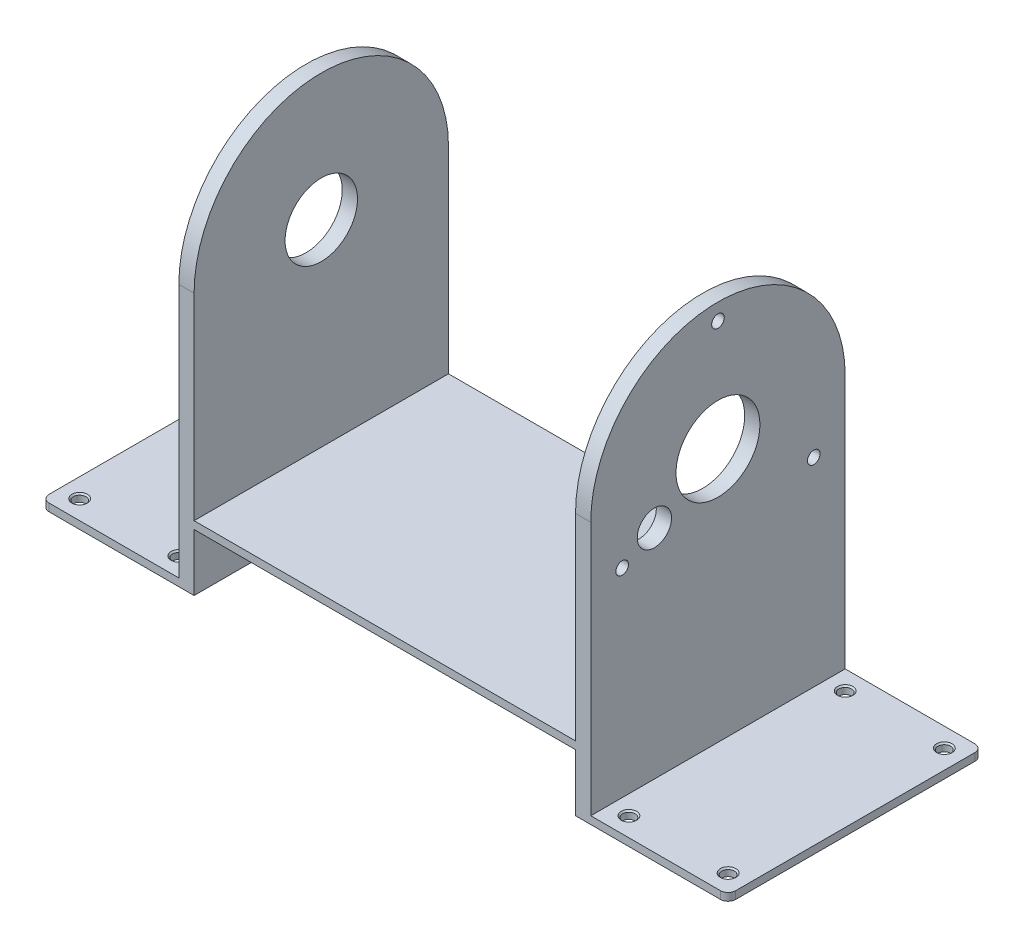
SolidWorks part; units mm, degrees
material "ABS"
ref_plane "前视基准面" through (0, 0, 0) normal (0, 0, 1) x (1, 0, 0)
ref_plane "上视基准面" through (0, 0, 0) normal (0, 1, 0) x (1, 0, 0)
ref_plane "右视基准面" through (0, 0, 0) normal (1, 0, 0) x (0, 0, -1)
sketch "草图1" plane through (0, 0, 0) normal (0, 1, 0) x (1, 0, 0)
  line L1 (-20, -33.35) -> (20, -33.35)
  line L2 (-20, -33.35) -> (-20, 33.35)
  line L3 (-20, 33.35) -> (20, 33.35)
  line L4 (20, -33.35) -> (20, 33.35)
  line L5 (-20, -33.35) -> (20, 33.35) construction
  line L6 (-20, 33.35) -> (20, -33.35) construction
  point P0 (0, 0)
  dimension "D1" = 40
  dimension "D2" = 66.7
extrude "凸台-拉伸1" add sketch "草图1" along normal blind 2
sketch "草图2" plane through (0, 2, 0) normal (0, 1, 0) x (1, 0, 0)
  line L0 (-20, -33.35) -> (20, -33.35) construction
  line L1 (-20, 33.35) -> (-16, 33.35)
  line L2 (-20, 33.35) -> (-20, -33.35)
  line L3 (-20, -33.35) -> (-16, -33.35)
  line L4 (-16, 33.35) -> (-16, -33.35)
  dimension "D1" = 4
extrude "凸台-拉伸2" add sketch "草图2" along normal blind 100
sketch "草图5" plane through (-20, 0, 0) normal (-1, 0, 0) x (0, 0, 1)
  line L0 (33.35, 102) -> (33.35, 0) construction
  line L1 (-33.35, 102) -> (33.35, 102) construction
  line L2 (33.35, 68.65) -> (33.35, 102)
  line L3 (33.35, 102) -> (0, 102)
  line L4 (0, 102) -> (-33.35, 102)
  line L5 (-33.35, 102) -> (-33.35, 68.65)
  circle A0 centre (0, 68.65) radius 33.35
  line M3 (33.35, 0) -> (33.35, 102)
  line M4 (33.35, 102) -> (-33.35, 102)
  line M5 (-33.35, 102) -> (-33.35, 0)
  dimension "D1" = 66.7
extrude "切除-拉伸1" cut sketch "草图5" against normal through all and the other way through all contours A0 M4 M5 | A0 M3 M4 | L2 L3 L4 L5
sketch "草图6" plane through (-20, 0, 0) normal (-1, 0, 0) x (0, 0, 1)
  line L0 (0, 68.65) -> (0, 97.65) construction
  line L1 (0, 68.65) -> (25.1147, 54.15) construction
  line L2 (0, 68.65) -> (-25.1147, 54.15) construction
  circle A0 centre (0, 68.65) radius 29 construction
  point P7 (0, 97.65)
  point P8 (25.1147, 54.15)
  point P9 (-25.1147, 54.15)
  point P10 (0, 68.65)
  dimension "D1" = 58
  dimension "D2" = 120
  dimension "D3" = 120
hole_wizard "M4 螺纹孔1" positions "草图7" profile "草图8" tap size "M4" standard "GB" end condition through all
sketch "草图7" plane through (-20, 0, 0) normal (-1, 0, 0) x (0, 0, 1)
  point P0 (0, 97.65)
  point P3 (25.1147, 54.15)
  point P6 (-25.1147, 54.15)
sketch "草图8" plane through (-20, 97.65, 0) normal (0, 1, 0) x (0, 0, 1)
  line L0 (0, 0) -> (0, 40)
  line L1 (0, 40) -> (1.65, 40)
  line L2 (1.65, 40) -> (1.65, 0.375)
  line L3 (1.65, 0.375) -> (2.025, 0)
  line L5 (2.025, 0) -> (0, 0)
  line L6 (-1.65, 0.375) -> (-2.025, 0) construction
  line L11 (0, -6.35) -> (0, 107.95) construction
  dimension "通孔螺纹孔钻头直径" = 3.3
  dimension "通孔螺纹孔钻头深度" = 40
  dimension "近端锥形沉头孔直径" = 4.05
  dimension "近端锥形沉头孔角度" = 90
sketch "草图9" plane through (0, 2, 0) normal (0, 1, 0) x (1, 0, 0)
  line L0 (-16, -33.35) -> (20, -33.35) construction
  line L1 (-11, 28.35) -> (15, 28.35) construction
  line L2 (-11, 28.35) -> (-11, -28.35) construction
  line L3 (-11, -28.35) -> (15, -28.35) construction
  line L4 (15, 28.35) -> (15, -28.35) construction
  line L5 (20, 33.35) -> (-16, 33.35) construction
  line L6 (20, -33.35) -> (20, 33.35) construction
  line L7 (-16, -33.35) -> (-16, 33.35) construction
  point P12 (-50.2188, 7.1013)
  point P13 (-11, 28.35)
  point P14 (-11, -28.35)
  point P15 (15, -28.35)
  point P16 (15, 28.35)
  dimension "D1" = 5
  dimension "D2" = 5
  dimension "D3" = 5
  dimension "D4" = 5
hole_wizard "M4 螺纹孔2" positions "草图9" profile "草图10" tap size "M4" standard "GB" end condition through all
sketch "草图10" plane through (15, 2, -28.35) normal (1, 0, 0) x (0, 0, 1)
  line L0 (0, 0) -> (0, 2)
  line L1 (0, 2) -> (1.65, 2)
  line L2 (1.65, 2) -> (1.65, 0.375)
  line L3 (1.65, 0.375) -> (2.025, 0)
  line L5 (2.025, 0) -> (0, 0)
  line L6 (-1.65, 0.375) -> (-2.025, 0) construction
  line L11 (0, -6.35) -> (0, 107.95) construction
  dimension "通孔螺纹孔钻头直径" = 3.3
  dimension "通孔螺纹孔钻头深度" = 2
  dimension "近端锥形沉头孔直径" = 4.05
  dimension "近端锥形沉头孔角度" = 90
sketch "草图11" plane through (-20, 0, 0) normal (-1, 0, 0) x (0, 0, 1)
  line L0 (-33.35, 68.65) -> (-33.35, 0) construction
  line L1 (-33.35, 17) -> (33.35, 17)
  line L2 (-33.35, 17) -> (-33.35, 15)
  line L3 (-33.35, 15) -> (33.35, 15)
  line L4 (33.35, 17) -> (33.35, 15)
  line L5 (33.35, 68.65) -> (33.35, 0) construction
  line L6 (-33.35, 0) -> (33.35, 0) construction
  dimension "D1" = 2
  dimension "D2" = 15
extrude "凸台-拉伸3" add sketch "草图11" along normal blind 100 contours L1 L4 L3 L2
ref_plane "基准面1" through (-70, 0, 0) normal (-1, 0, 0) x (0, 0, 1)
sketch "草图13" plane through (0, 0, 0) normal (0, 1, 0) x (1, 0, 0)
  line L0 (-120, -33.35) -> (-20, -33.35) construction
  line L1 (-120, 33.35) -> (-160, 33.35)
  line L2 (-120, 33.35) -> (-120, -33.35)
  line L3 (-120, -33.35) -> (-160, -33.35)
  line L4 (-160, 33.35) -> (-160, -33.35)
  dimension "D1" = 40
extrude "凸台-拉伸4" add sketch "草图13" along normal blind 2 separate body
sketch "草图14" plane through (0, 2, 0) normal (0, 1, 0) x (1, 0, 0)
  line L0 (-120, 33.35) -> (-120, -33.35) construction
  line L1 (-120, 33.35) -> (-124, 33.35)
  line L2 (-120, 33.35) -> (-120, -33.35)
  line L3 (-120, -33.35) -> (-124, -33.35)
  line L4 (-124, 33.35) -> (-124, -33.35)
  line L5 (-160, -33.35) -> (-120, -33.35) construction
  line L6 (-120, 33.35) -> (-160, 33.35) construction
  dimension "D1" = 4
extrude "凸台-拉伸5" add sketch "草图14" along normal blind 100
sketch "草图15" plane through (-124, 0, 0) normal (-1, 0, 0) x (0, 0, 1)
  line L0 (-33.35, 102) -> (33.35, 102) construction
  line L1 (33.35, 102) -> (33.35, 2) construction
  line L3 (33.35, 68.65) -> (33.35, 102)
  line L4 (33.35, 102) -> (0, 102)
  line L5 (0, 102) -> (-33.35, 102)
  line L6 (-33.35, 102) -> (-33.35, 61.9505)
  circle A0 centre (0, 68.65) radius 33.35
  line M3 (33.35, 2) -> (33.35, 102)
  line M4 (33.35, 102) -> (-33.35, 102)
  line M5 (-33.35, 102) -> (-33.35, 2)
  dimension "D1" = 66.7
extrude "切除-拉伸2" cut sketch "草图15" against normal through all and the other way through all contours A0 M4 M5 | A0 M3 M4 | L3 L4 L5 L6
sketch "草图16" plane through (0, 2, 0) normal (0, 1, 0) x (1, 0, 0)
  line L0 (-160, -33.35) -> (-124, -33.35) construction
  line L1 (-155, 28.35) -> (-129, 28.35) construction
  line L2 (-155, 28.35) -> (-155, -28.35) construction
  line L3 (-155, -28.35) -> (-129, -28.35) construction
  line L4 (-129, 28.35) -> (-129, -28.35) construction
  line L5 (-160, 33.35) -> (-160, -33.35) construction
  line L6 (-124, 33.35) -> (-160, 33.35) construction
  line L7 (-124, 33.35) -> (-124, -33.35) construction
  point P13 (-155, 28.35)
  point P14 (-155, -28.35)
  point P15 (-129, -28.35)
  point P16 (-129, 28.35)
  dimension "D1" = 5
  dimension "D2" = 5
  dimension "D3" = 5
  dimension "D4" = 5
hole_wizard "M4 螺纹孔3" positions "草图16" profile "草图17" tap size "M4" standard "GB" end condition through all
sketch "草图17" plane through (-129, 2, -28.35) normal (1, 0, 0) x (0, 0, 1)
  line L0 (0, 0) -> (0, 2)
  line L1 (0, 2) -> (1.65, 2)
  line L2 (1.65, 2) -> (1.65, 0.375)
  line L3 (1.65, 0.375) -> (2.025, 0)
  line L5 (2.025, 0) -> (0, 0)
  line L6 (-1.65, 0.375) -> (-2.025, 0) construction
  line L11 (0, -6.35) -> (0, 107.95) construction
  dimension "通孔螺纹孔钻头直径" = 3.3
  dimension "通孔螺纹孔钻头深度" = 2
  dimension "近端锥形沉头孔直径" = 4.05
  dimension "近端锥形沉头孔角度" = 90
cosmetic thread "孔螺纹线1" parameters "D2"=4
cosmetic thread "孔螺纹线2" parameters "D2"=4
cosmetic thread "孔螺纹线3" parameters "D2"=4
cosmetic thread "孔螺纹线4" parameters "D2"=4
sketch "草图18" plane through (-124, 0, 0) normal (-1, 0, 0) x (0, 0, 1)
  circle A0 centre (0, 68.65) radius 9.5
  dimension "D1" = 19
extrude "切除-拉伸3" cut sketch "草图18" against normal up to next
sketch "草图21" plane through (-16, 0, 0) normal (1, 0, 0) x (0, 0, -1)
  circle A0 centre (0, 68.65) radius 11
  dimension "D1" = 22
extrude "切除-拉伸4" cut sketch "草图21" against normal up to next
sketch "草图22" plane through (-16, 0, 0) normal (1, 0, 0) x (0, 0, -1)
  line L0 (-25.1147, 54.15) -> (0, 68.65) construction
  circle A0 centre (0, 68.65) radius 19.25 construction
  circle A2 centre (-16.671, 59.025) radius 4.5
  dimension "D1" = 38.5
  dimension "D2" = 9
extrude "切除-拉伸5" cut sketch "草图22" against normal up to next
fillet "圆角1" radius 2 4 edges at (20, 1, -33.35) (20, 1, 33.35) (-160, 1, 33.35) (-160, 1, -33.35)
